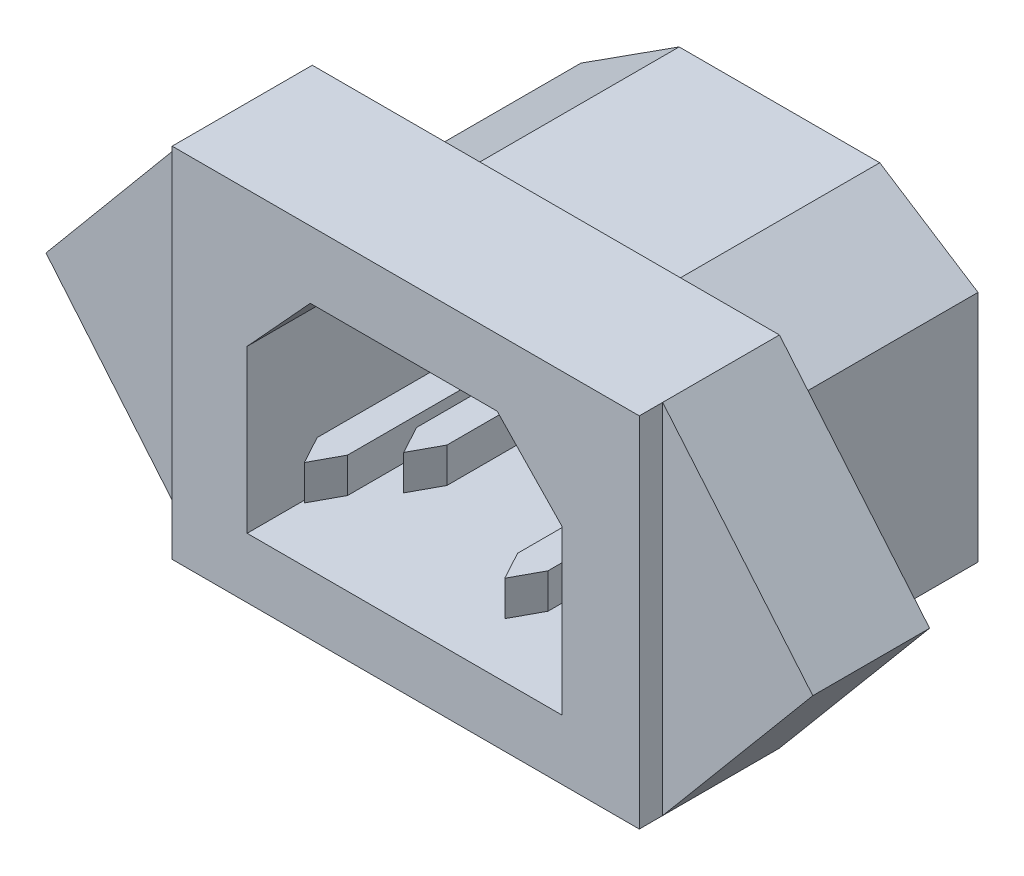
SolidWorks part; units mm, degrees
ref_plane "Front Plane" through (0, 0, 0) normal (0, 0, 1) x (1, 0, 0)
ref_plane "Top Plane" through (0, 0, 0) normal (0, 1, 0) x (1, 0, 0)
ref_plane "Right Plane" through (0, 0, 0) normal (1, 0, 0) x (0, 0, -1)
sketch "Sketch1" plane through (0, 0, 0) normal (0, 0, 1) x (1, 0, 0)
  line L0 (-22.4349, -6.6004) -> (-16.007, -14.2608)
  line L1 (-16.007, -14.2608) -> (-22.4349, -21.9213)
  line L2 (-22.4349, -6.6004) -> (-42.4349, -6.6004)
  line L3 (-22.4349, -21.9213) -> (-42.4349, -21.9213)
  line L6 (-22.4349, -21.9213) -> (-22.4349, -6.6004) construction
  line L7 (-42.4349, -21.9213) -> (-42.4349, -6.6004) construction
  line L9 (-42.4349, -6.6004) -> (-48.8349, -14.2608)
  line L10 (-42.4349, -21.9213) -> (-48.8349, -14.2608)
  point P2 (-22.4349, -14.2608)
  point P6 (-42.4349, -14.2608)
  dimension "D1" = 10
  dimension "D2" = 10
  dimension "D3" = 6.4279
  dimension "D4" = 50
  dimension "D5" = 20
  dimension "D6" = 20
  dimension "D7" = 6.4
  dimension "D8" = 50.123
extrude "Boss-Extrude1" add sketch "Sketch1" along normal blind 5
sketch "Sketch16" plane through (0, 0, 5) normal (0, 0, 1) x (1, 0, 0)
  line L0 (-42.4349, -21.9213) -> (-22.4349, -21.9213) construction
  line L1 (-42.4349, -6.6004) -> (-22.4349, -6.6004)
  line L2 (-42.4349, -6.6004) -> (-42.4349, -21.9213)
  line L3 (-42.4349, -21.9213) -> (-22.4349, -21.9213)
  line L4 (-22.4349, -6.6004) -> (-22.4349, -21.9213)
extrude "Boss-Extrude8" add sketch "Sketch16" along normal blind 1
sketch "Sketch17" plane through (0, 0, 0) normal (0, 0, -1) x (-1, 0, 0)
  line L0 (23.9349, -10.7723) -> (23.9349, -20.7723)
  line L1 (23.9349, -20.7723) -> (40.9349, -20.7723)
  line L2 (40.9349, -20.7723) -> (40.9349, -10.7723)
  line L3 (40.9349, -10.7723) -> (36.729, -8.0685)
  line L4 (36.729, -8.0685) -> (28.1408, -8.0685)
  line L5 (28.1408, -8.0685) -> (23.9349, -10.7723)
  point P5 (39.812, -12.3222)
  point P7 (41.6171, -10.223)
  dimension "D1" = 8.5882
  dimension "D2" = 5
  dimension "D3" = 5
  dimension "D4" = 10
  dimension "D5" = 1.5
  dimension "D6" = 1.5
  dimension "D7" = 17
extrude "Boss-Extrude9" add sketch "Sketch17" along normal blind 10
sketch "Sketch18" plane through (0, 0, 6) normal (0, 0, 1) x (1, 0, 0)
  line L0 (-36.5211, -9.4692) -> (-28.5211, -9.4692)
  line L1 (-28.5211, -9.4692) -> (-25.7452, -12.3491)
  line L2 (-25.7452, -12.3491) -> (-25.7452, -19.3496)
  line L3 (-25.7452, -19.3496) -> (-39.2248, -19.3496)
  line L4 (-39.2248, -19.3496) -> (-39.2248, -12.4171)
  line L5 (-39.2248, -12.4171) -> (-36.5211, -9.4692)
  point P6 (-25.1174, -12.2383)
  dimension "D1" = 4
  dimension "D2" = 4
  dimension "D3" = 8
extrude "Cut-Extrude5" cut sketch "Sketch18" against normal blind 15
ref_plane "Plane11" through (0, -17, 0) normal (0, 1, 0) x (1, 0, 0)
sketch "Sketch19" plane through (0, -17, 0) normal (0, 1, 0) x (1, 0, 0)
  line L0 (-39.2248, 9) -> (-25.7452, 9) construction
  line L1 (-27.5452, 9) -> (-28.8452, 9)
  line L2 (-27.5452, 9) -> (-27.5452, -4.8)
  line L4 (-28.8452, 9) -> (-28.8452, -4.8)
  line L5 (-28.1952, 9) -> (-28.1952, -6) construction
  line L6 (-36.1248, 9) -> (-37.4248, 9)
  line L7 (-36.1248, 9) -> (-36.1248, -4.8)
  line L9 (-37.4248, 9) -> (-37.4248, -4.8)
  line L10 (-39.2248, -6) -> (-25.7452, -6) construction
  line L11 (-36.7748, 9) -> (-36.7748, -6) construction
  line L12 (-27.5452, -4.8) -> (-28.1952, -6)
  line L13 (-28.1952, -6) -> (-28.8452, -4.8)
  line L14 (-36.1248, -4.8) -> (-36.7748, -6)
  line L15 (-36.7748, -6) -> (-37.4248, -4.8)
  point P10 (-28.1952, 9)
  point P11 (-36.7748, 9)
  dimension "D1" = 1.3
  dimension "D2" = 1.3
  dimension "D3" = 13.8
  dimension "D4" = 13.8
  dimension "D5" = 1.8
  dimension "D6" = 1.8
extrude "Boss-Extrude10" add sketch "Sketch19" along normal blind 1.5
ref_plane "Plane12" through (0, -13, 0) normal (0, -1, 0) x (-1, 0, 0)
sketch "Sketch20" plane through (0, -13, 0) normal (0, -1, 0) x (-1, 0, 0)
  line L0 (28.5211, 9) -> (36.5211, 9) construction
  line L1 (33.1711, 9) -> (31.8711, 9)
  line L2 (33.1711, 9) -> (33.1711, -4.8)
  line L4 (31.8711, 9) -> (31.8711, -4.8)
  line L5 (32.5211, 9) -> (32.5211, -6) construction
  line L8 (33.1711, -4.8) -> (32.5211, -6)
  line L9 (32.5211, -6) -> (31.8711, -4.8)
  point P6 (32.5211, 9)
  point P8 (32.5211, 9)
  dimension "D1" = 1.3
  dimension "D2" = 13.8
  dimension "D3" = 0
extrude "Boss-Extrude11" add sketch "Sketch20" along normal blind 1.5
sketch "Sketch22" plane through (0, 0, -9) normal (0, 0, 1) x (1, 0, 0)
  line L1 (-27.5452, -17) -> (-28.8452, -17)
  line L2 (-27.5452, -17) -> (-27.5452, -15.5)
  line L3 (-27.5452, -15.5) -> (-28.8452, -15.5)
  line L4 (-28.8452, -17) -> (-28.8452, -15.5)
  line L5 (-31.8711, -14.5) -> (-33.1711, -14.5)
  line L6 (-31.8711, -14.5) -> (-31.8711, -13)
  line L7 (-31.8711, -13) -> (-33.1711, -13)
  line L8 (-33.1711, -14.5) -> (-33.1711, -13)
  line L9 (-36.1248, -17) -> (-37.4248, -17)
  line L10 (-36.1248, -17) -> (-36.1248, -15.5)
  line L11 (-36.1248, -15.5) -> (-37.4248, -15.5)
  line L12 (-37.4248, -17) -> (-37.4248, -15.5)
extrude "Cut-Extrude6" cut sketch "Sketch22" against normal up to next
sketch "Sketch23" plane through (0, 0, -10) normal (0, 0, -1) x (-1, 0, 0)
  line L0 (37.4248, -17) -> (37.4248, -15.5) construction
  line L1 (37.9044, -18) -> (35.6044, -18)
  line L2 (37.9044, -18) -> (37.9044, -14.5)
  line L3 (37.9044, -14.5) -> (35.6044, -14.5)
  line L4 (35.6044, -18) -> (35.6044, -14.5)
  line L5 (29.3452, -18) -> (29.3452, -14.5)
  line L7 (29.3452, -18) -> (27.0452, -18)
  line L8 (27.0452, -18) -> (27.0452, -14.5)
  line L9 (29.3452, -14.5) -> (27.0452, -14.5)
  point P4 (37.4248, -16.25)
  point P7 (37.9044, -16.25)
  dimension "D1" = 2.3
  dimension "D2" = 0.4796
  dimension "D3" = 2
  dimension "D4" = 3.5
  dimension "D5" = 0.5
  dimension "D6" = 2.3
extrude "Boss-Extrude12" add sketch "Sketch23" along normal blind 1.5
sketch "Sketch24" plane through (0, 0, -10) normal (0, 0, -1) x (-1, 0, 0)
  line L0 (33.1711, -14.5) -> (33.1711, -13) construction
  line L1 (33.6711, -15.5) -> (31.3711, -15.5)
  line L2 (33.6711, -15.5) -> (33.6711, -12)
  line L3 (33.6711, -12) -> (31.3711, -12)
  line L4 (31.3711, -15.5) -> (31.3711, -12)
  line L5 (33.1711, -13.75) -> (35.0817, -13.75) construction
  point P4 (33.1711, -13.75)
  point P6 (33.6711, -13.75)
  dimension "D1" = 0.5
  dimension "D2" = 2.3
  dimension "D3" = 3.5
  dimension "D4" = 0
extrude "Boss-Extrude13" add sketch "Sketch24" along normal blind 1.5
sketch "Sketch25" plane through (0, 0, -11.5) normal (0, 0, -1) x (-1, 0, 0)
  line L0 (31.3711, -12) -> (31.3711, -15.5) construction
  line L1 (32.7211, -15) -> (32.3211, -15)
  line L2 (32.7211, -15) -> (32.7211, -12.5)
  line L3 (32.7211, -12.5) -> (32.3211, -12.5)
  line L4 (32.3211, -15) -> (32.3211, -12.5)
  line L5 (31.3711, -15.5) -> (33.6711, -15.5) construction
  line L6 (32.5211, -15) -> (32.5211, -13.75) construction
  line L7 (32.5211, -13.75) -> (32.3211, -13.75) construction
  line L8 (32.5211, -13.75) -> (32.5211, -15.5) construction
  line L9 (32.5211, -13.75) -> (31.3711, -13.75) construction
  point P4 (31.3711, -13.75)
  point P5 (32.5211, -15.5)
  point P8 (32.5211, -13.75)
  point P11 (32.5211, -15)
  point P12 (32.3211, -13.75)
  point P13 (32.5211, -13.75)
  dimension "D1" = 0.4
  dimension "D2" = 2.5
  dimension "D3" = 0
  dimension "D4" = 0
extrude "Boss-Extrude14" add sketch "Sketch25" along normal blind 2
sketch "Sketch26" plane through (0, 0, -11.5) normal (0, 0, -1) x (-1, 0, 0)
  line L0 (36.5544, -16.25) -> (36.7544, -16.25) construction
  line L1 (36.9544, -17.5) -> (36.5544, -17.5)
  line L2 (36.9544, -17.5) -> (36.9544, -15)
  line L3 (36.9544, -15) -> (36.5544, -15)
  line L4 (36.5544, -17.5) -> (36.5544, -15)
  line L5 (36.7544, -16.25) -> (36.7544, -17.5) construction
  line L6 (35.6044, -14.5) -> (35.6044, -18) construction
  line L7 (35.6044, -18) -> (37.9044, -18) construction
  line L8 (36.7544, -18) -> (36.7544, -16.25) construction
  line L9 (36.7544, -16.25) -> (35.6044, -16.25) construction
  line L10 (27.0452, -14.5) -> (27.0452, -18) construction
  line L11 (27.0452, -18) -> (29.3452, -18) construction
  line L12 (28.1952, -18) -> (28.1952, -16.25) construction
  line L14 (28.3952, -17.5) -> (28.3952, -15)
  line L15 (28.3952, -17.5) -> (27.9952, -17.5)
  line L16 (27.9952, -17.5) -> (27.9952, -15)
  line L17 (28.3952, -15) -> (27.9952, -15)
  line L18 (28.1952, -17.5) -> (28.1952, -16.25) construction
  line L19 (28.1952, -16.25) -> (27.9952, -16.25) construction
  point P4 (36.5544, -16.25)
  point P5 (36.7544, -17.5)
  point P6 (36.7544, -16.25)
  point P9 (36.7544, -18)
  point P11 (35.6044, -16.25)
  point P12 (36.7544, -16.25)
  point P19 (28.1952, -18)
  point P21 (27.0452, -16.25)
  point P22 (28.1952, -16.25)
  point P29 (28.1952, -17.5)
  point P31 (27.9952, -16.25)
  dimension "D1" = 0.4
  dimension "D2" = 2.5
  dimension "D3" = 0
  dimension "D4" = 0
  dimension "D7" = 0
  dimension "D5" = 2
extrude "Boss-Extrude15" add sketch "Sketch26" along normal blind 2
